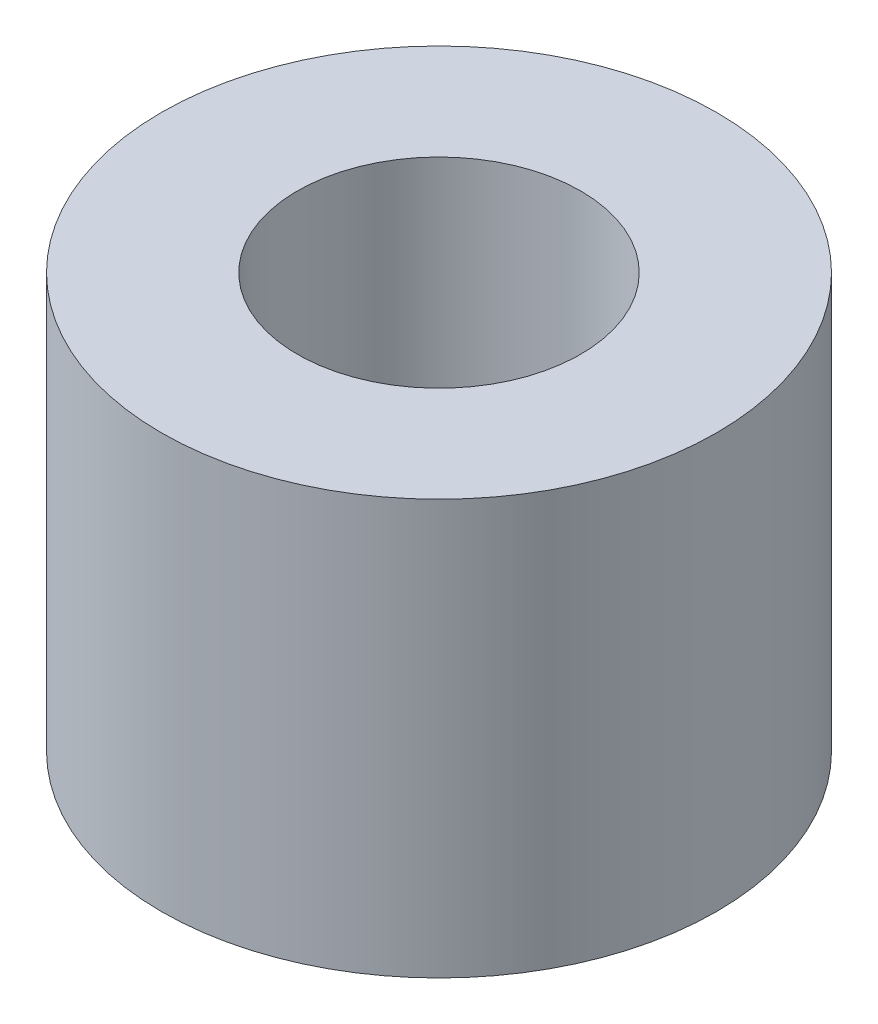
SolidWorks part; units mm, degrees
ref_plane "Front Plane" through (0, 0, 0) normal (0, 0, 1) x (1, 0, 0)
ref_plane "Top Plane" through (0, 0, 0) normal (0, 1, 0) x (1, 0, 0)
ref_plane "Right Plane" through (0, 0, 0) normal (1, 0, 0) x (0, 0, -1)
sketch "Sketch1" plane through (0, 0, 0) normal (0, 1, 0) x (1, 0, 0)
  circle A0 centre (0, 0) radius 3.175
  circle A1 centre (0, 0) radius 6.223
  dimension "D1" = 3.048
  dimension "D2" = 6.35
extrude "Boss-Extrude1" add sketch "Sketch1" along normal blind 9.2964
